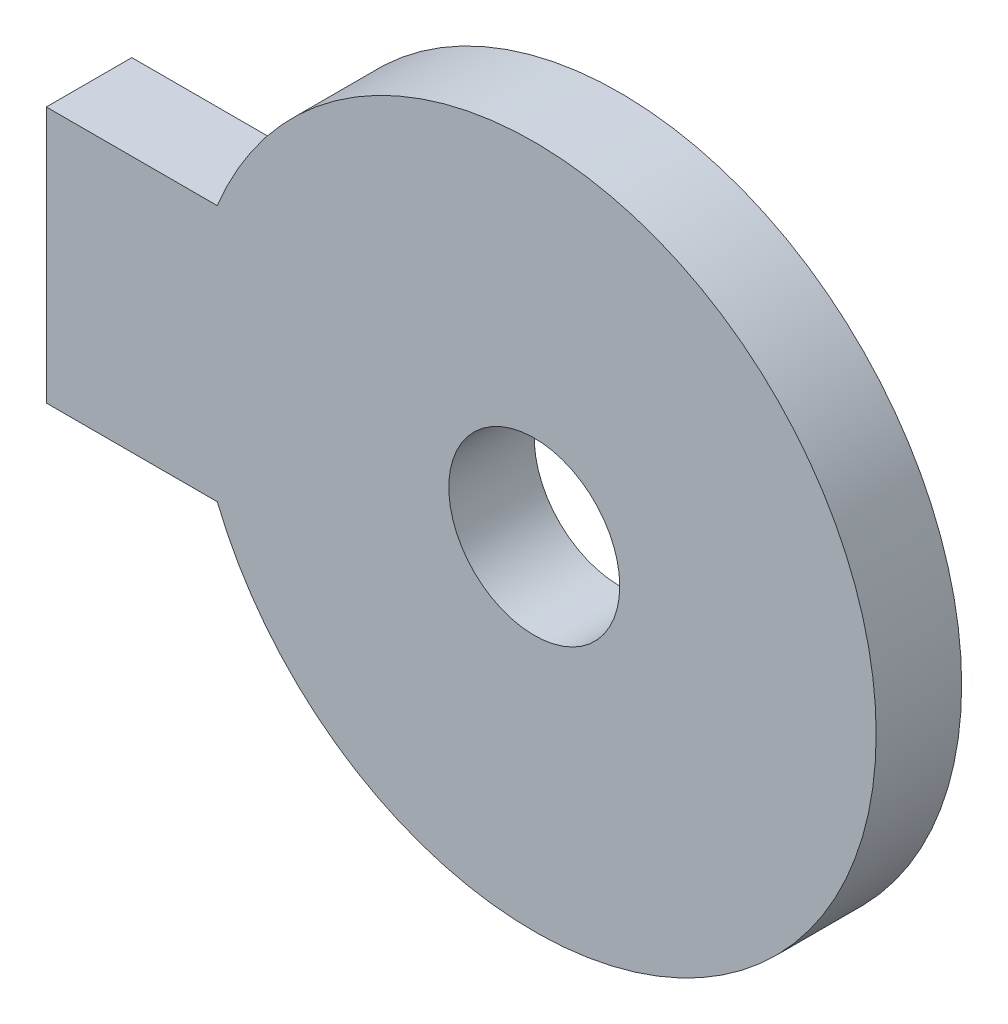
SolidWorks part; units mm, degrees
ref_plane "Front Plane" through (0, 0, 0) normal (0, 0, 1) x (1, 0, 0)
ref_plane "Top Plane" through (0, 0, 0) normal (0, 1, 0) x (1, 0, 0)
ref_plane "Right Plane" through (0, 0, 0) normal (1, 0, 0) x (0, 0, -1)
sketch "Sketch1" plane through (0, 0, 0) normal (0, 0, 1) x (1, 0, 0)
  line L0 (-28.5405, -7.5) -> (-28.5405, 7.5)
  line L1 (-28.5405, 7.5) -> (-18.5405, 7.5)
  line L2 (-28.5405, -7.5) -> (-18.5405, -7.5)
  circle A0 centre (0, 0) radius 5
  arc A1 (-18.5405, -7.5) -> (-18.5405, 7.5) centre (0, 0) ccw
  point P7 (-28.5405, 0)
  dimension "D1" = 10
  dimension "D2" = 20
  dimension "D3" = 15
  dimension "D4" = 10
extrude "Boss-Extrude1" add sketch "Sketch1" along normal blind 5
